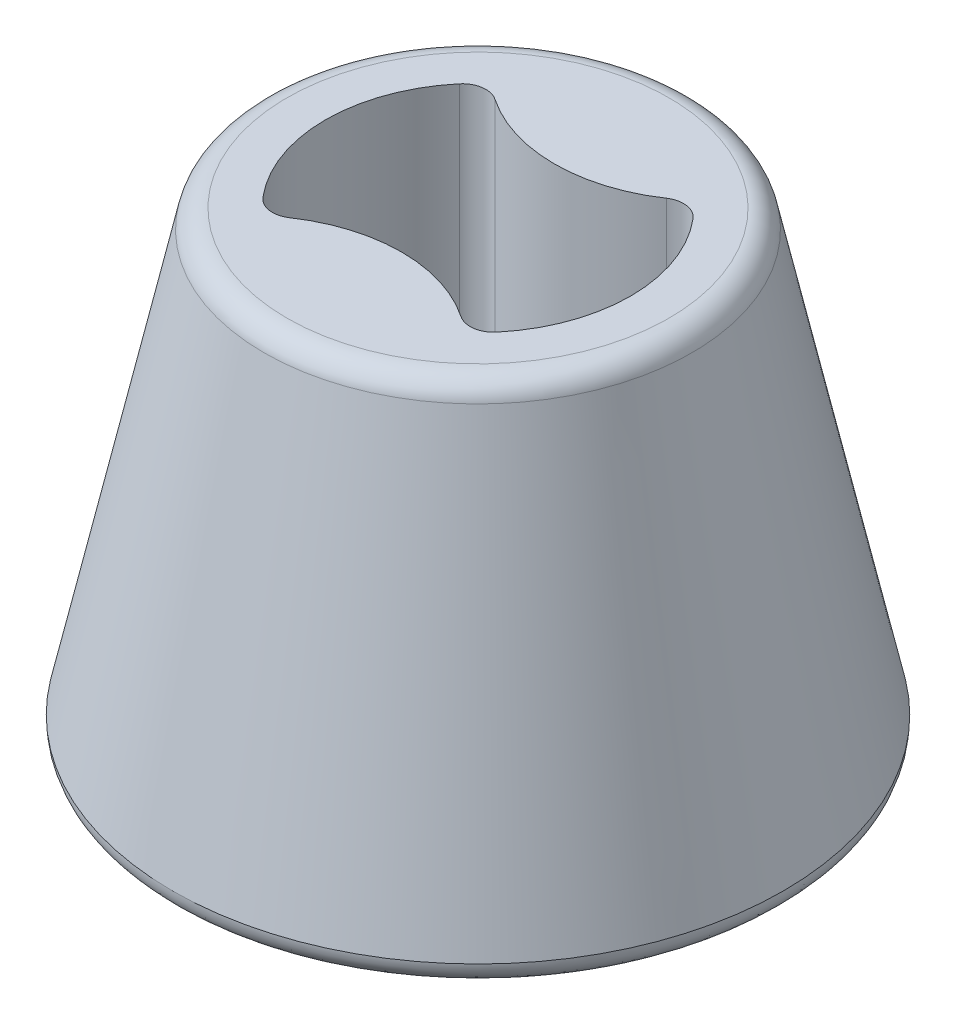
SolidWorks part; units mm, degrees
material "Rubber"
ref_plane "Front Plane" through (0, 0, 0) normal (0, 0, 1) x (1, 0, 0)
ref_plane "Top Plane" through (0, 0, 0) normal (0, 1, 0) x (1, 0, 0)
ref_plane "Right Plane" through (0, 0, 0) normal (1, 0, 0) x (0, 0, -1)
sketch "Sketch1" plane through (0, 0, 0) normal (0, 0, 1) x (1, 0, 0)
  line L0 (0, 0) -> (16, 0)
  line L1 (0, 0) -> (0, 23)
  line L2 (0, 23) -> (11, 23)
  line L3 (11, 23) -> (16, 0)
revolve "Revolve2" add sketch "Sketch1" angle 360 about L1
sketch "Sketch3" plane through (0, 0, 0) normal (0, 0, 1) x (1, 0, 0)
  line L0 (0, 0) -> (0, -2)
  line L3 (16, 0) -> (10, 0)
  line L4 (-16, 0) -> (16, 0) construction
  line L5 (10, 0) -> (5, 0)
  line L6 (0, 0) -> (16, 0)
  arc A1 (4.0001, -1.9889) -> (5.9998, -1.9517) centre (4.9999, -1.9703) ccw
  arc A2 (9.0013, -1.8444) -> (10.9982, -1.7333) centre (9.9998, -1.7889) ccw
  spline S0 degree 3 poles (16, 0) (16.0056, -0.8674) (14.5027, -1.4583) (12.6248, -1.6225) (11.3592, -1.7101) (10.9982, -1.7333) knots 0 0 0 0 0.112319 0.275651 0.340734 0.340734 0.340734 0.340734
  spline S1 degree 2 poles (4.0001, -1.9889) (2.0009, -2.0141) (0, -2) knots 0.760292 0.760292 0.760292 1 1 1
  spline S2 degree 3 poles (9.0013, -1.8444) (8.5041, -1.8679) (7.5033, -1.9091) (6.5029, -1.9391) (5.9998, -1.9517) knots 0.460547 0.460547 0.460547 0.460547 0.549936 0.640415 0.640415 0.640415 0.640415
revolve "Revolve3" add sketch "Sketch3" angle 360 about L0
scale "Scale1" scale about origin uniform scaling yes scale factor 0.8125
sketch "Sketch4" plane through (0, 18.6875, 0) normal (0, 1, 0) x (1, 0, 0)
  arc A0 (4.973, -4.1856) -> (4.973, 4.1856) centre (0, 0) ccw
  arc A2 (-3.6469, 4.3694) -> (3.6469, 4.3694) centre (0, 9.75) ccw
  arc A3 (3.6469, -4.3694) -> (-3.6469, -4.3694) centre (0, -9.75) ccw
  arc A4 (-4.973, 4.1856) -> (-4.973, -4.1856) centre (0, 0) ccw
  arc A5 (-4.973, -4.1856) -> (-3.6469, -4.3694) centre (-4.2079, -3.5417) ccw
  arc A6 (4.973, -4.1856) -> (3.6469, -4.3694) centre (4.2079, -3.5417) cw
  arc A7 (-3.6469, 4.3694) -> (-4.973, 4.1856) centre (-4.2079, 3.5417) ccw
  arc A8 (3.6469, 4.3694) -> (4.973, 4.1856) centre (4.2079, 3.5417) cw
  point P15 (-4.2993, 4.875)
  dimension "D1" = 1
extrude "Cut-Extrude1" cut sketch "Sketch4" against normal blind 10
fillet "Fillet1" radius 1 1 edges at (0, 18.6875, -8.9375)
